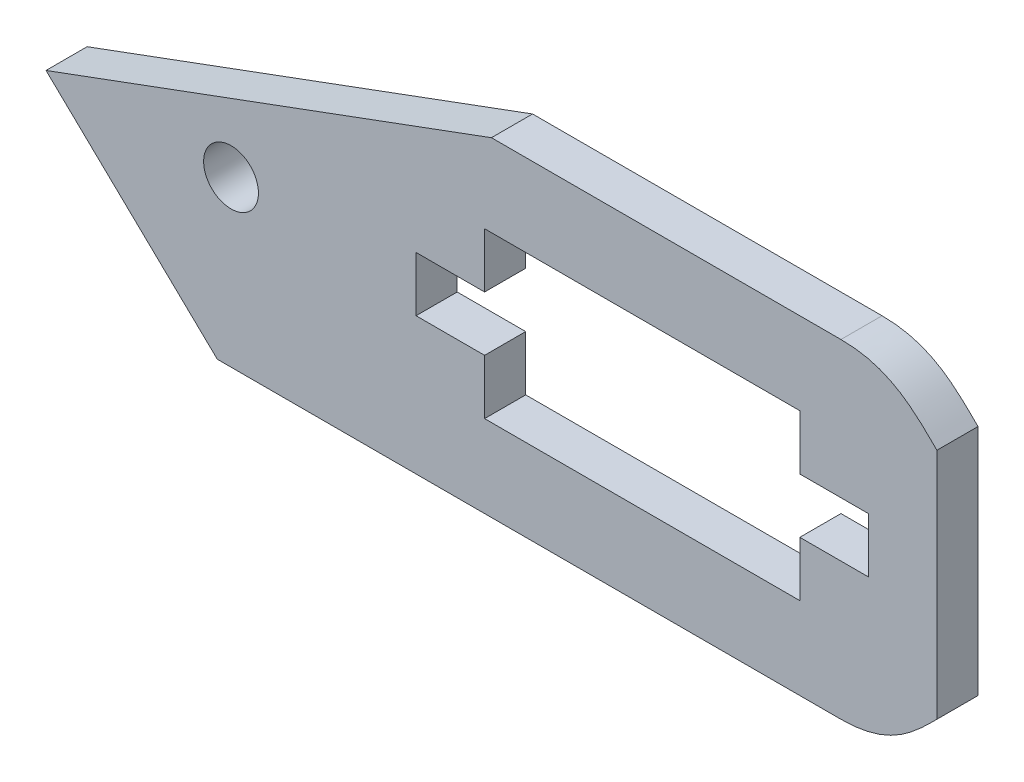
SolidWorks part; units mm, degrees
ref_plane "Plan de face" through (0, 0, 0) normal (0, 0, 1) x (1, 0, 0)
ref_plane "Plan de dessus" through (0, 0, 0) normal (0, 1, 0) x (1, 0, 0)
ref_plane "Plan de droite" through (0, 0, 0) normal (1, 0, 0) x (0, 0, -1)
sketch "Esquisse1" plane through (0, 0, 0) normal (0, 0, 1) x (1, 0, 0)
  line L0 (-34.4015, 0) -> (-21.9015, -12)
  line L1 (30.5985, -12) -> (-34.4015, -12)
  line L3 (30.5985, 12) -> (-34.4015, 12)
  line L4 (-34.4015, -12) -> (-34.4015, 12)
  line L5 (30.5985, -12) -> (-34.4015, 12) construction
  line L6 (30.5985, 12) -> (-34.4015, -12) construction
  line L7 (30.5985, 12) -> (30.5985, -12)
  line L20 (-34.4015, 0) -> (-1.9015, 12)
  line L21 (-2.4015, 6) -> (20.5985, 6)
  line L22 (-2.4015, 6) -> (-2.4015, -6)
  line L23 (-2.4015, -6) -> (20.5985, -6)
  line L24 (20.5985, 6) -> (20.5985, -6)
  line L25 (-2.4015, 2) -> (-7.4015, 2)
  line L26 (-2.4015, 2) -> (-2.4015, -2)
  line L27 (-2.4015, -2) -> (-7.4015, -2)
  line L28 (-7.4015, 2) -> (-7.4015, -2)
  line L29 (20.5985, 2) -> (25.5985, 2)
  line L30 (20.5985, 2) -> (20.5985, -2)
  line L31 (20.5985, -2) -> (25.5985, -2)
  line L32 (25.5985, 2) -> (25.5985, -2)
  line L33 (30.5985, 5) -> (37.5985, 5) construction
  line L34 (37.5985, 5) -> (37.5985, -5) construction
  line L35 (37.5985, -5) -> (30.5985, -5) construction
  line L36 (23.5985, 12) -> (30.5985, 12) construction
  line L37 (30.5985, 12) -> (30.5985, 5) construction
  line L38 (30.5985, 5) -> (37.5985, 5) construction
  line L39 (23.5985, -12) -> (30.5985, -12) construction
  line L40 (30.5985, -12) -> (30.5985, -5) construction
  line L41 (30.5985, -5) -> (37.5985, -5) construction
  spline S0 degree 3 poles (23.5985, 12) (30.5985, 12) (30.5985, 5) (37.5985, 5) knots 0 0 0 0 1 1 1 1
  spline S1 degree 3 poles (23.5985, -12) (30.5985, -12) (30.5985, -5) (37.5985, -5) knots 0 0 0 0 1 1 1 1
  point P8 (14.2956, 0.3737)
  dimension "D12" = 5
  dimension "D1" = 24
  dimension "D2" = 65
  dimension "D3" = 12
  dimension "D4" = 4
  dimension "D5" = 4
  dimension "D6" = 5
  dimension "D7" = 6
  dimension "D8" = 10
  dimension "D9" = 23
  dimension "D10" = 4
  dimension "D11" = 4
  dimension "D13" = 7
  dimension "D14" = 7
  dimension "D15" = 7
  dimension "D16" = 7
extrude "Boss.-Extru.1" add sketch "Esquisse1" along normal blind 3
sketch "Sketch1" plane through (0, 0, 3) normal (0, 0, 1) x (1, 0, 0)
  line L0 (-34.4015, 0) -> (-7.4015, 0) construction
  line L1 (-7.4015, 2) -> (-7.4015, -2) construction
  circle A0 centre (-20.9015, 0) radius 2
  dimension "D1" = 4
extrude "Cut-Extrude1" cut sketch "Sketch1" against normal through all
